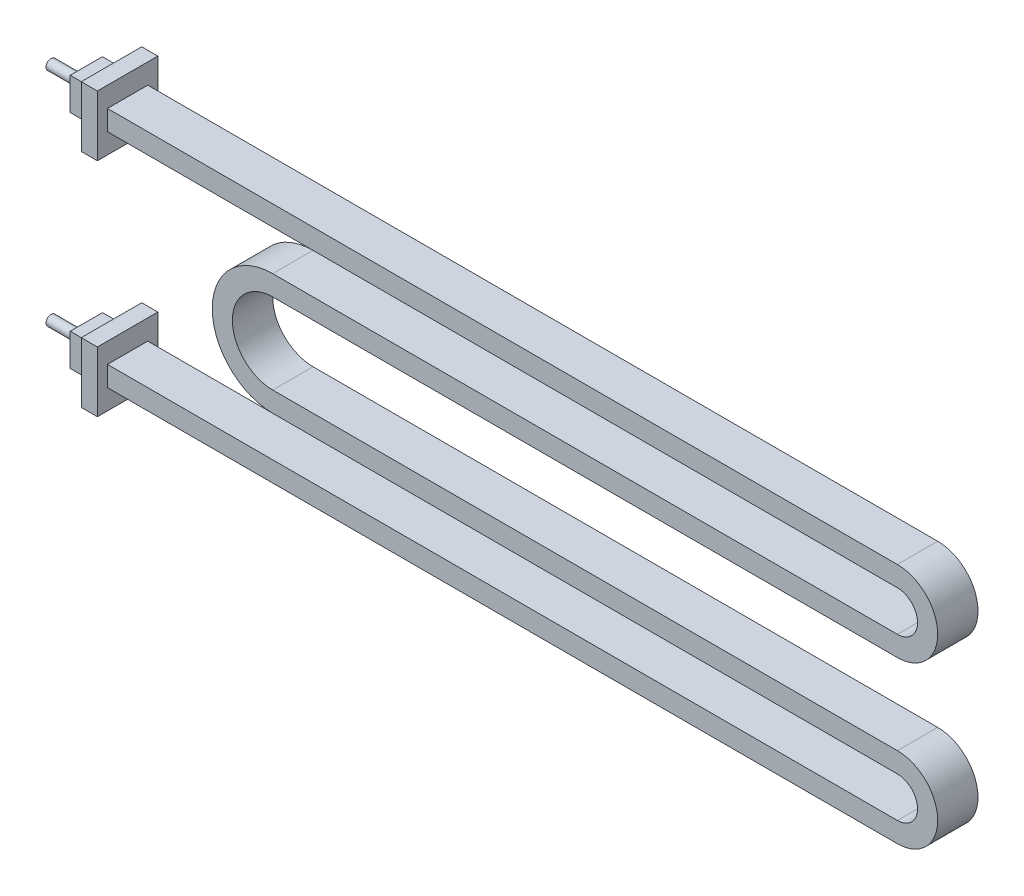
SolidWorks part; units mm, degrees
ref_plane "Alzado" through (0, 0, 0) normal (0, 0, 1) x (1, 0, 0)
ref_plane "Planta" through (0, 0, 0) normal (0, 1, 0) x (1, 0, 0)
ref_plane "Vista lateral" through (0, 0, 0) normal (1, 0, 0) x (0, 0, -1)
sketch "Sketch1" plane through (0, 0, 0) normal (0, 0, 1) x (1, 0, 0)
  line L0 (0, 0) -> (200, 0)
  line L1 (200, -20) -> (45, -20)
  line L2 (45, -40) -> (200, -40)
  line L3 (200, -60) -> (0, -60)
  line L4 (0, -5) -> (200, -5)
  line L5 (200, -15) -> (45, -15)
  line L6 (45, -45) -> (200, -45)
  line L7 (200, -55) -> (0, -55)
  line L8 (0, 0) -> (0, -5)
  line L9 (0, -55) -> (0, -60)
  arc A0 (200, 0) -> (200, -20) centre (200, -10) cw
  arc A1 (45, -20) -> (45, -40) centre (45, -30) ccw
  arc A2 (200, -40) -> (200, -60) centre (200, -50) cw
  arc A3 (200, -5) -> (200, -15) centre (200, -10) cw
  arc A4 (45, -15) -> (45, -45) centre (45, -30) ccw
  arc A5 (200, -45) -> (200, -55) centre (200, -50) cw
  point P11 (0, 0)
  point P24 (0, 0)
  dimension "D1" = 10
  dimension "D2" = 10
  dimension "D3" = 10
  dimension "D4" = 200
  dimension "D5" = 155
  dimension "D7" = 5
extrude "Boss-Extrude1" add sketch "Sketch1" along normal blind 10
sketch "Sketch2" plane through (0, 0, 0) normal (-1, 0, 0) x (0, 0, 1)
  line L0 (5, -5) -> (5, 0) construction
  line L1 (10, -5) -> (0, -5) construction
  line L2 (10, 0) -> (0, 0) construction
  circle A0 centre (5, -2.5) radius 1.25
  dimension "D1" = 2.5
extrude "Boss-Extrude2" add sketch "Sketch2" along normal blind 15
sketch "Sketch3" plane through (0, 0, 0) normal (-1, 0, 0) x (0, 0, 1)
  line L0 (5, -60) -> (5, -55) construction
  line L1 (10, -60) -> (0, -60) construction
  line L2 (10, -55) -> (0, -55) construction
  circle A0 centre (5, -57.5) radius 1.25
  dimension "D1" = 2.5
extrude "Boss-Extrude3" add sketch "Sketch3" along normal blind 15
sketch "Sketch4" plane through (0, 0, 0) normal (1, 0, 0) x (0, 0, -1)
  line L0 (-5, 0) -> (-5, -60) construction
  line L1 (-10, 0) -> (0, 0) construction
  line L2 (-10, -60) -> (0, -60) construction
  line L3 (0, -30) -> (-10, -30) construction
  line L4 (-10, -15) -> (-10, -45) construction
  line L5 (0, -2.5) -> (-10, -2.5) construction
  line L6 (-10, 0) -> (-10, -5) construction
  line L7 (2.5, -50) -> (-12.5, -50)
  line L9 (-5, -2.5) -> (-3.75, -2.5)
  line L10 (2.5, 5) -> (-12.5, 5)
  line L11 (2.5, 5) -> (2.5, -10)
  line L12 (2.5, -10) -> (-12.5, -10)
  line L13 (-12.5, 5) -> (-12.5, -10)
  line L14 (2.5, 5) -> (-12.5, -10) construction
  line L15 (2.5, -10) -> (-12.5, 5) construction
  line L16 (-12.5, -65) -> (-12.5, -50)
  line L17 (2.5, -65) -> (-12.5, -65)
  line L18 (2.5, -65) -> (2.5, -50)
  circle A0 centre (-5, -2.5) radius 1.25 construction
  point P11 (-5, -30)
  point P17 (-5, -2.5)
  point P30 (0, 0)
  dimension "D1" = 15
  dimension "D2" = 15
extrude "Boss-Extrude5" add sketch "Sketch4" along normal blind 4 separate body
sketch "Sketch5" plane through (0, 0, 0) normal (-1, 0, 0) x (0, 0, 1)
  line L0 (5, 5) -> (5, -65) construction
  line L1 (-2.5, 5) -> (12.5, 5) construction
  line L2 (-2.5, -65) -> (12.5, -65) construction
  line L3 (-6.9096, -30) -> (16.9096, -30) construction
  line L4 (1, -53.5) -> (9, -53.5)
  line L5 (1, 1.5) -> (9, 1.5)
  line L6 (1, 1.5) -> (1, -6.5)
  line L7 (1, -6.5) -> (9, -6.5)
  line L8 (9, 1.5) -> (9, -6.5)
  line L9 (1, 1.5) -> (9, -6.5) construction
  line L10 (1, -6.5) -> (9, 1.5) construction
  line L11 (9, -61.5) -> (9, -53.5)
  line L12 (1, -61.5) -> (9, -61.5)
  line L13 (1, -61.5) -> (1, -53.5)
  point P6 (5, -2.5)
  point P9 (5, -30)
  dimension "D1" = 8
  dimension "D2" = 8
extrude "Boss-Extrude6" add sketch "Sketch5" along normal blind 6.25 separate body
